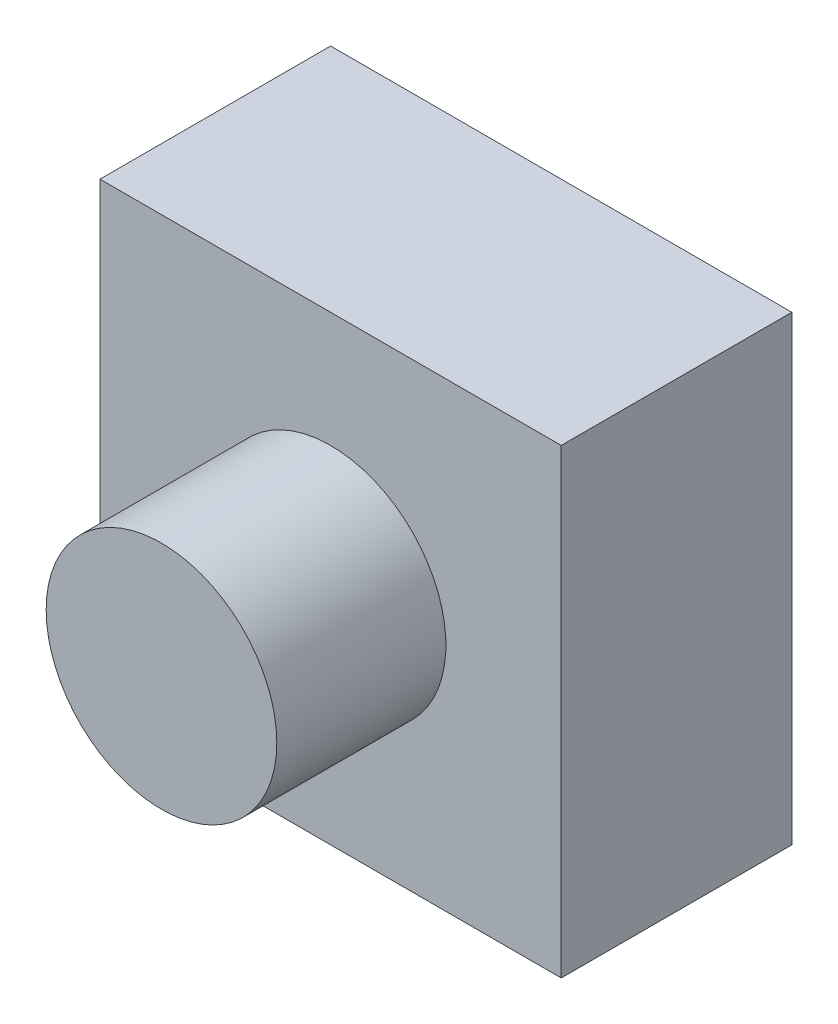
SolidWorks part; units mm, degrees
ref_plane "Front Plane" through (0, 0, 0) normal (0, 0, 1) x (1, 0, 0)
ref_plane "Top Plane" through (0, 0, 0) normal (0, 1, 0) x (1, 0, 0)
ref_plane "Right Plane" through (0, 0, 0) normal (1, 0, 0) x (0, 0, -1)
sketch "Sketch2" plane through (0, 0, 0) normal (0, 0, 1) x (1, 0, 0)
  line L1 (-3, -3) -> (3, -3)
  line L2 (-3, -3) -> (-3, 3)
  line L3 (-3, 3) -> (3, 3)
  line L4 (3, -3) -> (3, 3)
  line L5 (-3, -3) -> (3, 3) construction
  line L6 (-3, 3) -> (3, -3) construction
  point P0 (0, 0)
  dimension "D1" = 6
  dimension "D2" = 6
extrude "Boss-Extrude1" add sketch "Sketch2" along normal blind 3
sketch "Sketch3" plane through (0, 0, 3) normal (0, 0, 1) x (1, 0, 0)
  circle A0 centre (0, 0) radius 1.5
  dimension "D1" = 3
extrude "Boss-Extrude2" add sketch "Sketch3" along normal blind 2.2 contours A0
